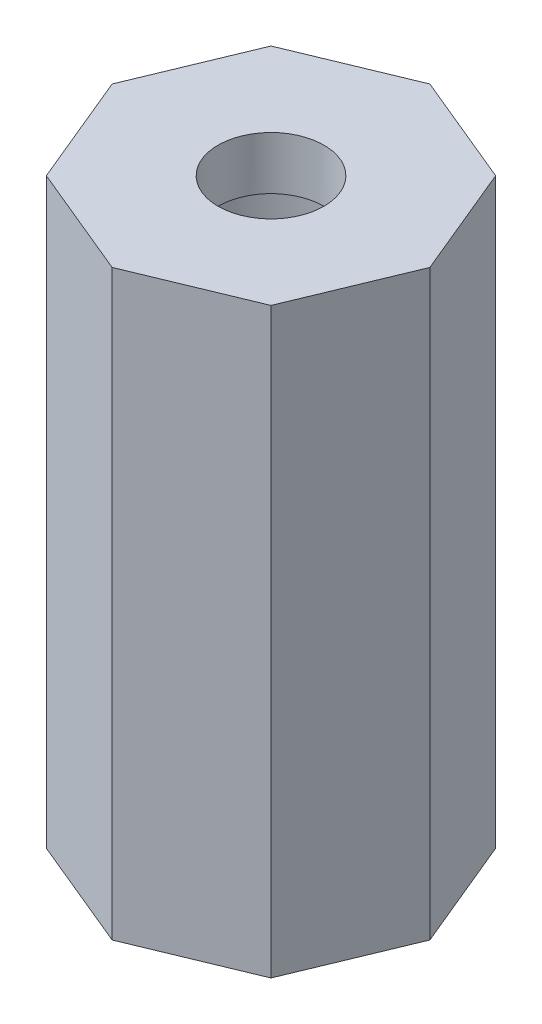
SolidWorks part; units mm, degrees
ref_plane "Front Plane" through (0, 0, 0) normal (0, 0, 1) x (1, 0, 0)
ref_plane "Top Plane" through (0, 0, 0) normal (0, 1, 0) x (1, 0, 0)
ref_plane "Right Plane" through (0, 0, 0) normal (1, 0, 0) x (0, 0, -1)
sketch "Sketch1" plane through (0, 0, 0) normal (0, 1, 0) x (1, 0, 0)
  line L1 (30, 0) -> (21.2132, 21.2132)
  line L2 (21.2132, 21.2132) -> (0, 30)
  line L3 (0, 30) -> (-21.2132, 21.2132)
  line L4 (-21.2132, 21.2132) -> (-30, 0)
  line L5 (-30, 0) -> (-21.2132, -21.2132)
  line L6 (-21.2132, -21.2132) -> (0, -30)
  line L7 (0, -30) -> (21.2132, -21.2132)
  line L8 (21.2132, -21.2132) -> (30, 0)
  circle A0 centre (0, 0) radius 27.7164 construction
  dimension "D1" = 30
extrude "Boss-Extrude1" add sketch "Sketch1" along normal blind 110
sketch "Sketch2" plane through (0, 110, 0) normal (0, 1, 0) x (1, 0, 0)
  circle A0 centre (0, 0) radius 10
extrude "Cut-Extrude1" cut sketch "Sketch2" against normal blind 110 contours A0
sketch "Sketch3" plane through (0, 0, 0) normal (0, -1, 0) x (1, 0, 0)
  circle A0 centre (0, 0) radius 20
extrude "Cut-Extrude2" cut sketch "Sketch3" against normal blind 100 contours A0
